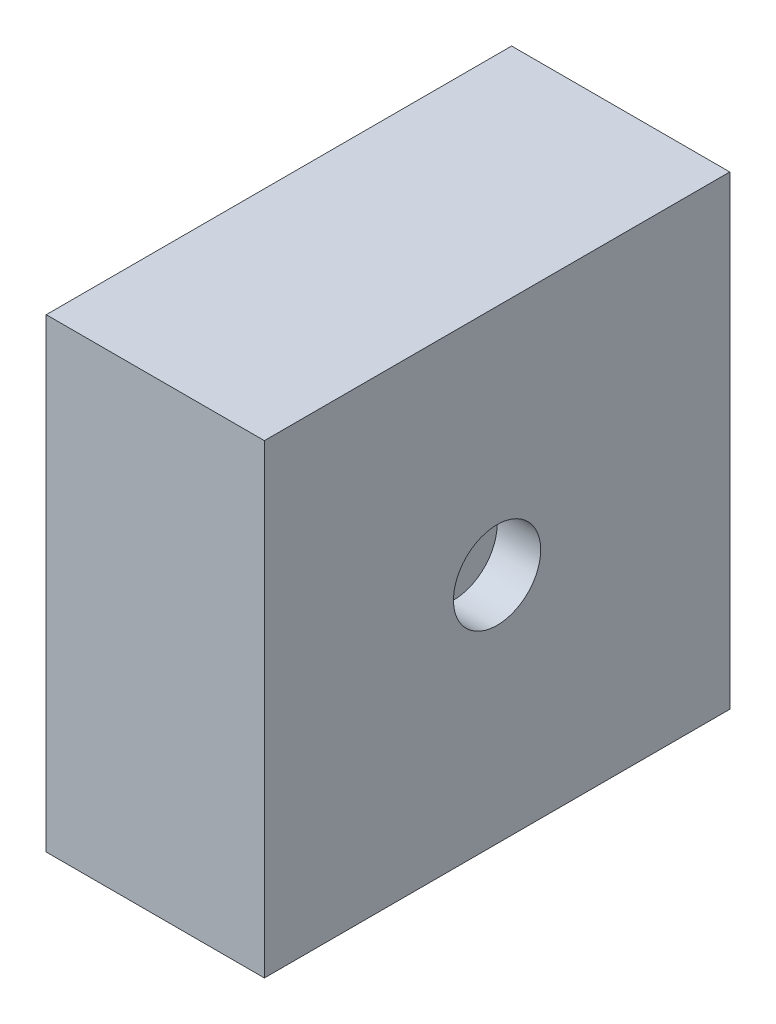
SolidWorks part; units mm, degrees
ref_plane "Front Plane" through (0, 0, 0) normal (0, 0, 1) x (1, 0, 0)
ref_plane "Top Plane" through (0, 0, 0) normal (0, 1, 0) x (1, 0, 0)
ref_plane "Right Plane" through (0, 0, 0) normal (1, 0, 0) x (0, 0, -1)
sketch "Sketch2" plane through (0, 0, 0) normal (1, 0, 0) x (0, 0, -1)
  line L1 (0, 0) -> (-32, 0)
  line L2 (0, 0) -> (0, -32)
  line L3 (0, -32) -> (-32, -32)
  line L4 (-32, 0) -> (-32, -32)
  dimension "D1" = 32
  dimension "D2" = 32
extrude "Boss-Extrude1" add sketch "Sketch2" along normal blind 15
sketch "Sketch3" plane through (15, 0, 0) normal (1, 0, 0) x (0, 0, -1)
  line L0 (0, 0) -> (-32, 0) construction
  line L1 (0, -32) -> (0, 0) construction
  circle A0 centre (-16, -16) radius 3
  dimension "D1" = 6
  dimension "D2" = 16
  dimension "D3" = 16
extrude "Cut-Extrude1" cut sketch "Sketch3" against normal blind 3
